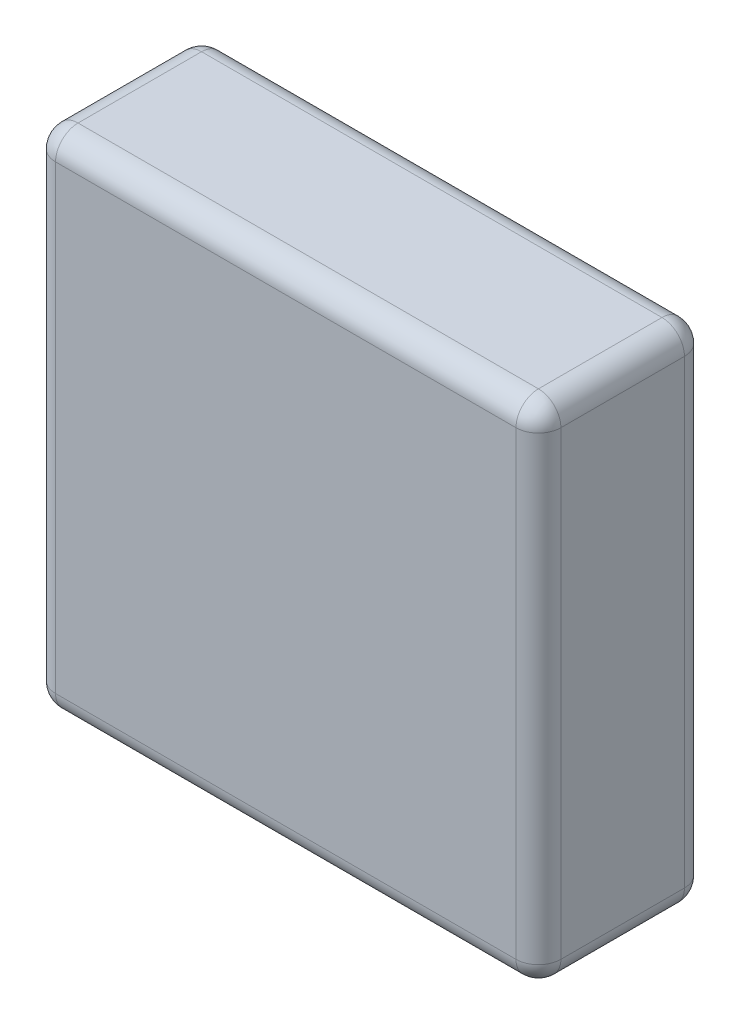
SolidWorks part; units mm, degrees
ref_plane "前视基准面" through (0, 0, 0) normal (0, 0, 1) x (1, 0, 0)
ref_plane "上视基准面" through (0, 0, 0) normal (0, 1, 0) x (1, 0, 0)
ref_plane "右视基准面" through (0, 0, 0) normal (1, 0, 0) x (0, 0, -1)
sketch "草图1" plane through (0, 0, 0) normal (0, 0, 1) x (1, 0, 0)
  line L1 (-45, -45) -> (45, -45)
  line L2 (-45, -45) -> (-45, 45)
  line L3 (-45, 45) -> (45, 45)
  line L4 (45, -45) -> (45, 45)
  line L5 (-45, -45) -> (45, 45) construction
  line L6 (-45, 45) -> (45, -45) construction
  point P0 (0, 0)
  dimension "D1" = 90
  dimension "D2" = 90
extrude "凸台-拉伸1" add sketch "草图1" along normal blind 30
fillet "圆角1" radius 4 12 edges at (-45, 45, 15) (45, 45, 15) (-45, -45, 15) (45, -45, 15) (0, 45, 0) (-45, 0, 0) (0, -45, 0) (45, 0, 0) (0, -45, 30) (-45, 0, 30) (0, 45, 30) (45, 0, 30)
